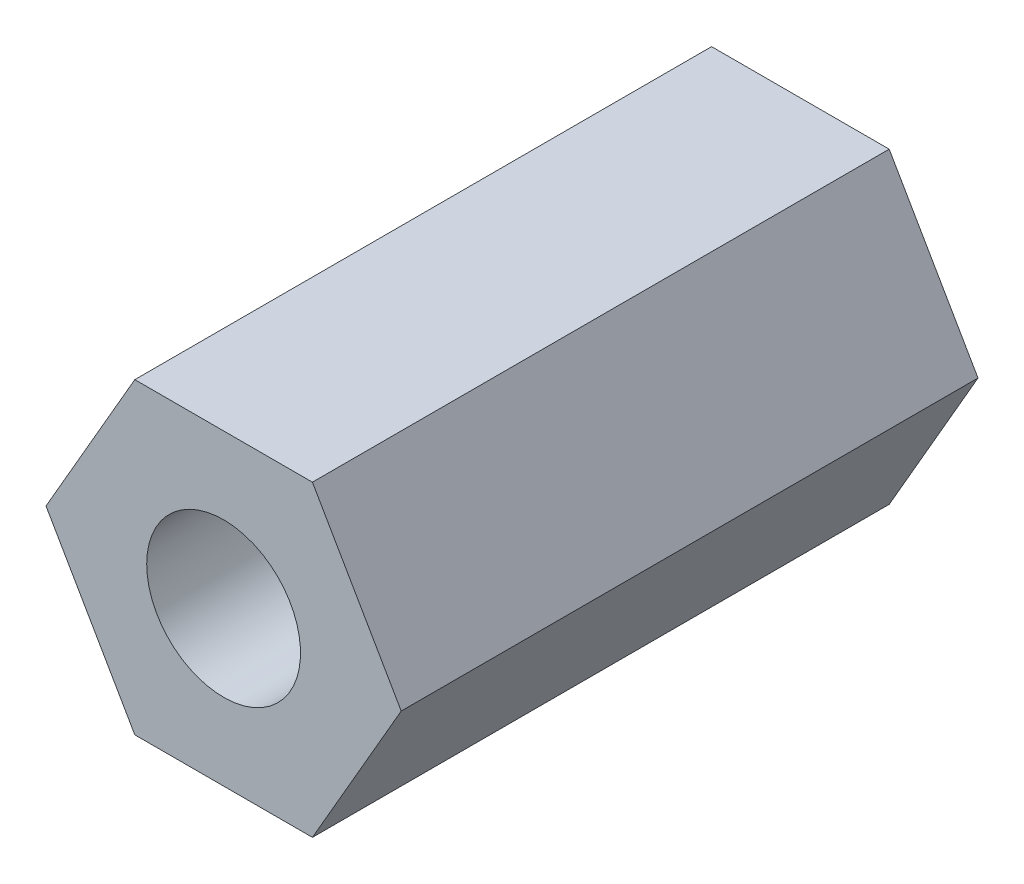
SolidWorks part; units mm, degrees
ref_plane "前视基准面" through (0, 0, 0) normal (0, 0, 1) x (1, 0, 0)
ref_plane "上视基准面" through (0, 0, 0) normal (0, 1, 0) x (1, 0, 0)
ref_plane "右视基准面" through (0, 0, 0) normal (1, 0, 0) x (0, 0, -1)
sketch "草图1" plane through (0, 0, 0) normal (0, 0, 1) x (1, 0, 0)
  line L0 (-28.6627, 0) -> (33.6774, 0) construction
  line L1 (0.9238, -1.6) -> (1.8475, 0)
  line L2 (1.8475, 0) -> (0.9238, 1.6)
  line L3 (0.9238, 1.6) -> (-0.9238, 1.6)
  line L4 (-0.9238, 1.6) -> (-1.8475, 0)
  line L5 (-1.8475, 0) -> (-0.9238, -1.6)
  line L6 (-0.9238, -1.6) -> (0.9238, -1.6)
  circle A0 centre (0, 0) radius 1.6 construction
  dimension "D1" = 3.2
extrude "拉伸1" add sketch "草图1" along normal blind 6
sketch "草图2" plane through (0, 0, 6) normal (0, 0, 1) x (1, 0, 0)
  circle A0 centre (0, 0) radius 1
  dimension "D1" = 2
hole_wizard "M2 螺纹孔1" positions "3D草图2" profile "草图5" tap size "M2" standard "Iso"
sketch3d "3D草图2"
  point P0 (0, 0, 0)
  point P2 (0, 0, 0)
  point P3 (0, 0, 0)
  point P4 (0, 0, 0)
cosmetic thread "孔螺蚊线1" parameters "D1"=4, "D2"=2
sketch "草图5" plane through (0, 0, 0) normal (1, 0, 0) x (0, 1, 0)
  line L0 (0, 0) -> (0, 6.4807)
  line L1 (0, 6.4807) -> (0.8, 6)
  line L2 (0.8, 6) -> (0.8, 0)
  line L5 (0.8, 0) -> (0, 0)
  line L10 (0, 6.4807) -> (-0.8, 6) construction
  line L11 (0, -6.35) -> (0, 107.95) construction
  dimension "蹟恇謂郰芛眻噤" = 1.6
  dimension "蹟恇謂郰芛旮僅" = 6
  dimension "絳芛褒僅" = 118
cosmetic thread "孔螺蚊线2" parameters "D1"=4, "D2"=2
cosmetic thread "孔螺蚊线3" parameters "D1"=4, "D2"=2
cosmetic thread "孔螺蚊线4" parameters "D1"=4, "D2"=2
sketch "草图6" plane through (0, 0, 0) normal (0, 0, -1) x (-1, 0, 0)
  circle A0 centre (0, 0) radius 1.5
  dimension "D1" = 3
extrude "拉伸3" [suppressed] add sketch "草图6" along normal blind 10
